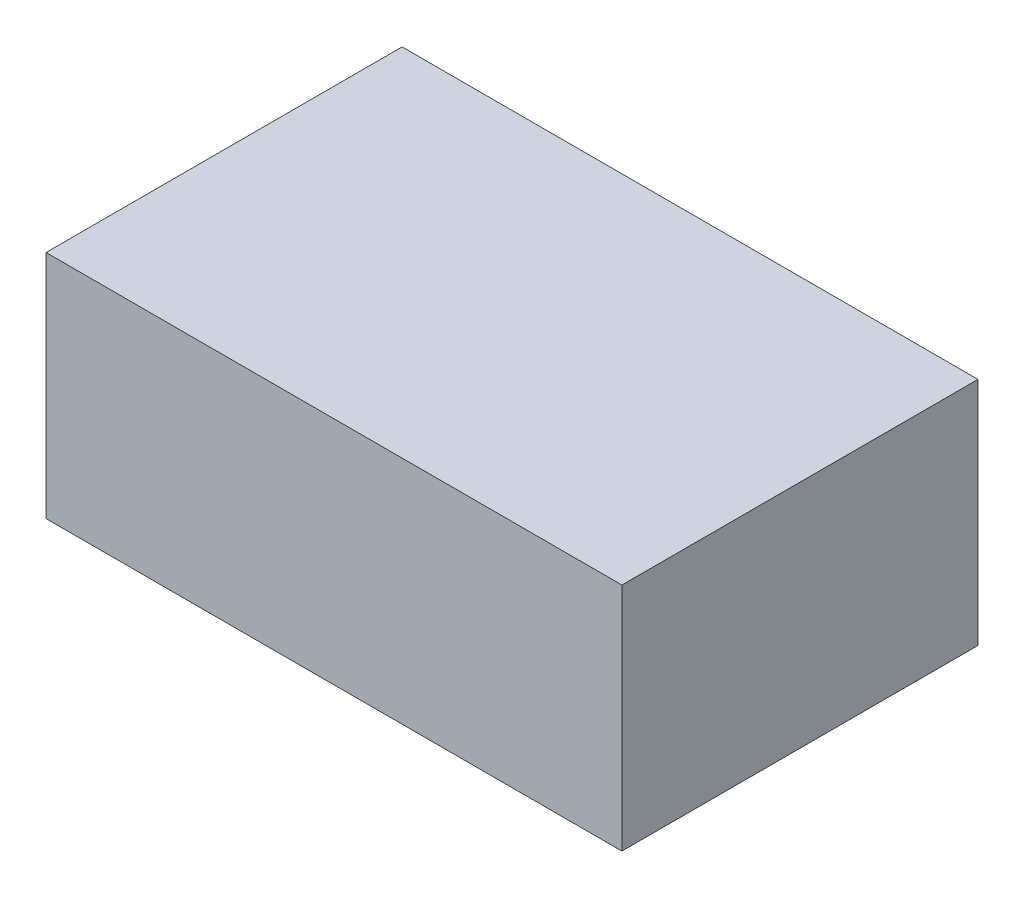
SolidWorks part; units mm, degrees
material "Cast Alloy Steel"
ref_plane "Front Plane" through (0, 0, 0) normal (0, 0, 1) x (1, 0, 0)
ref_plane "Top Plane" through (0, 0, 0) normal (0, 1, 0) x (1, 0, 0)
ref_plane "Right Plane" through (0, 0, 0) normal (1, 0, 0) x (0, 0, -1)
sketch "Sketch1" plane through (0, 0, 0) normal (0, 1, 0) x (1, 0, 0)
  line L1 (0, 98.1221) -> (158.6855, 98.1221)
  line L2 (0, 98.1221) -> (0, 0)
  line L3 (0, 0) -> (158.6855, 0)
  line L4 (158.6855, 98.1221) -> (158.6855, 0)
  point P4 (0, 0)
  point P6 (158.6855, 98.1221)
extrude "Boss-Extrude1" add sketch "Sketch1" along normal blind 63.5
